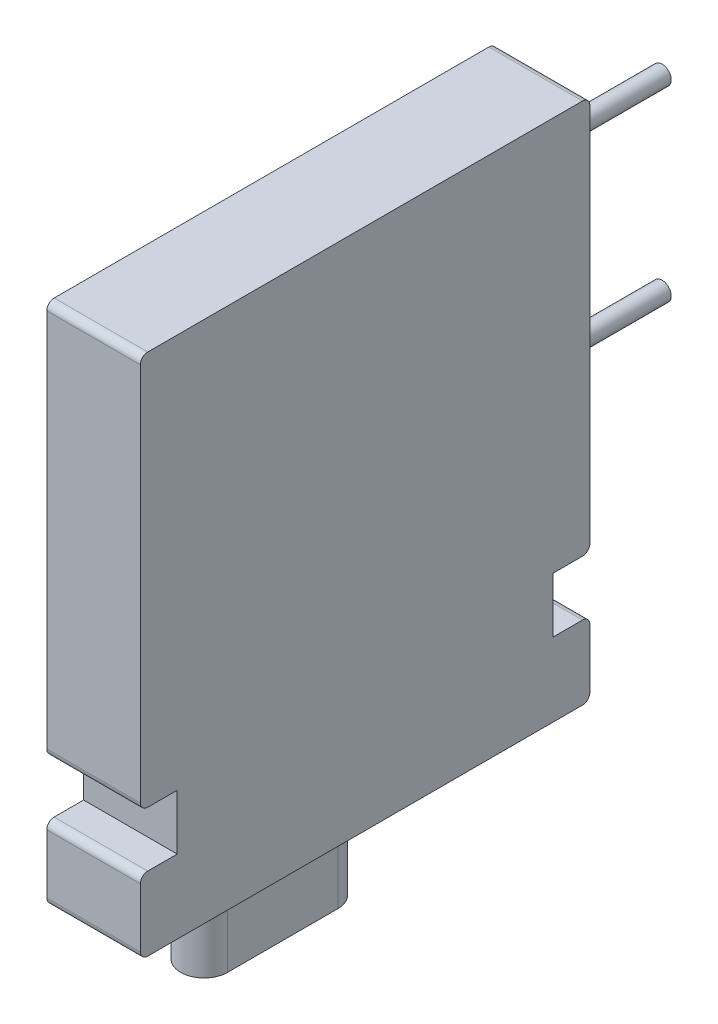
SolidWorks part; units mm, degrees
ref_plane "前视基准面" through (0, 0, 0) normal (0, 0, 1) x (1, 0, 0)
ref_plane "上视基准面" through (0, 0, 0) normal (0, 1, 0) x (1, 0, 0)
ref_plane "右视基准面" through (0, 0, 0) normal (1, 0, 0) x (0, 0, -1)
sketch "草图1" plane through (0, 0, 0) normal (0, 0, 1) x (1, 0, 0)
  line L1 (0, 0) -> (2.54, 0)
  line L2 (0, 0) -> (0, 14.2)
  line L3 (0, 14.2) -> (2.54, 14.2)
  line L4 (2.54, 0) -> (2.54, 14.2)
  point P5 (1.27, 0)
  dimension "D1" = 2.54
  dimension "D2" = 14.2
extrude "凸台-拉伸1" add sketch "草图1" along normal blind 12.2
sketch "草图2" plane through (0, 0, 0) normal (0, 0, -1) x (-1, 0, 0)
  line L0 (0, 14.2) -> (0, 0) construction
  line L1 (-2.54, 14.2) -> (0, 14.2) construction
  circle A0 centre (-1.5, 12.7) radius 0.25
  circle A1 centre (-1.5, 7.62) radius 0.25
  point P8 (0, 7.1)
  dimension "D1" = 0.5
  dimension "D2" = 1.5
  dimension "D3" = 1.5
  dimension "D4" = 0.5
  dimension "D5" = 5.08
  dimension "D6" = 1.5
extrude "凸台-拉伸2" add sketch "草图2" along normal blind 3
sketch "草图3" plane through (0, 0, 0) normal (0, -1, 0) x (-1, 0, 0)
  line L0 (-1.27, -9.2) -> (-1.27, -6.2) construction
  line L1 (-1.905, -9.2) -> (-1.905, -6.2)
  line L2 (-0.635, -9.2) -> (-0.635, -6.2)
  line L3 (0, -12.2) -> (0, 0) construction
  line L6 (0, -12.2) -> (-2.54, -12.2) construction
  arc A0 (-1.905, -9.2) -> (-0.635, -9.2) centre (-1.27, -9.2) ccw
  arc A1 (-0.635, -6.2) -> (-1.905, -6.2) centre (-1.27, -6.2) ccw
  point P2 (-1.27, -7.7)
  dimension "D3" = 3
  dimension "D4" = 3
  dimension "D1" = 1.27
  dimension "D2" = 1.27
extrude "凸台-拉伸3" add sketch "草图3" along normal blind 2.1
sketch "草图4" plane through (0, 0, 0) normal (0, -1, 0) x (1, 0, 0)
  line L0 (1.27, 12.2) -> (1.27, 0) construction
  line L1 (0, 12.2) -> (2.54, 12.2) construction
  line L2 (0, 0) -> (2.54, 0) construction
  line L3 (0.27, 3.5) -> (0.27, 1.5)
  line L4 (0.27, 3.5) -> (2.27, 3.5)
  line L6 (0.27, 1.5) -> (2.27, 1.5)
  line L7 (2.27, 3.5) -> (2.27, 1.5)
  point P10 (1.27, 3.5)
  point P11 (1.27, 1.5)
  point P13 (1.27, 1.5)
  point P14 (1.27, 3.5)
  dimension "D1" = 1
  dimension "D2" = 1.5
  dimension "D3" = 2
extrude "切除-拉伸1" cut sketch "草图4" against normal blind 5
sketch "草图5" plane through (2.54, 0, 0) normal (1, 0, 0) x (0, 0, -1)
  line L0 (-12.2, 0) -> (0, 0) construction
  line L1 (-13.7975, 3.5) -> (-11.2, 3.5)
  line L2 (-13.7975, 3.5) -> (-13.7975, 2)
  line L3 (-13.7975, 2) -> (-11.2, 2)
  line L4 (-11.2, 3.5) -> (-11.2, 2)
  line L5 (-1, 3.5) -> (1.6553, 3.5)
  line L6 (-1, 3.5) -> (-1, 2)
  line L7 (-1, 2) -> (1.6553, 2)
  line L8 (1.6553, 3.5) -> (1.6553, 2)
  line L9 (-12.2, 0) -> (-12.2, 14.2) construction
  line L10 (0, 0) -> (0, 14.2) construction
  point P10 (-11.2, 2.75)
  point P13 (-1, 2.75)
  dimension "D1" = 2
  dimension "D2" = 2
  dimension "D3" = 1.5
  dimension "D4" = 1.5
  dimension "D5" = 1
  dimension "D6" = 1
extrude "切除-拉伸2" cut sketch "草图5" against normal up to next
fillet "圆角1" radius 0.2 8 edges at (1.27, 3.5, 0) (1.27, 2, 0) (1.27, 3.5, 12.2) (1.27, 2, 12.2) (1.27, 14.2, 0) (1.27, 14.2, 12.2) (1.27, 0, 0) (1.27, 0, 12.2)
